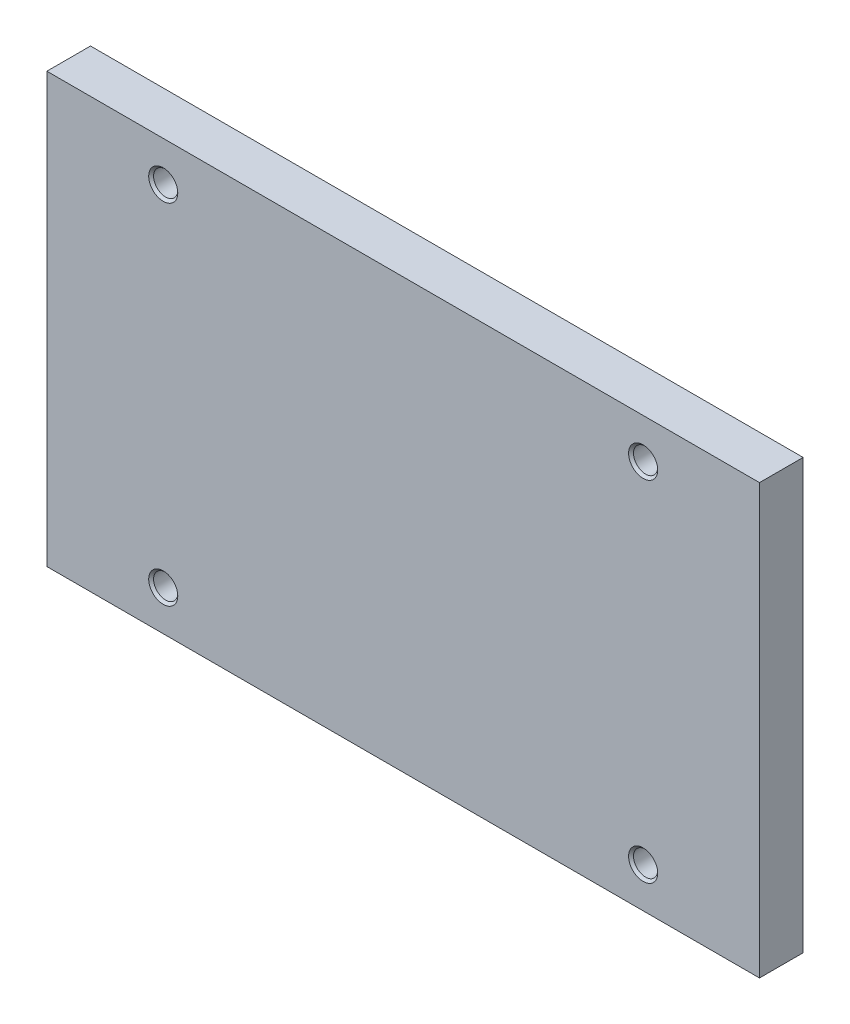
SolidWorks part; units mm, degrees
ref_plane "Спереди" through (0, 0, 0) normal (0, 0, 1) x (1, 0, 0)
ref_plane "Сверху" through (0, 0, 0) normal (0, 1, 0) x (1, 0, 0)
ref_plane "Справа" through (0, 0, 0) normal (1, 0, 0) x (0, 0, -1)
ref_plane "Плоскость4" through (0, 0, 12) normal (0, 0, 1) x (1, 0, 0)
sketch "Эскиз1" plane through (0, 0, 12) normal (0, 0, 1) x (1, 0, 0)
  line L0 (98, 59) -> (-98, 59)
  line L1 (-98, 59) -> (-98, -59)
  line L2 (-98, -59) -> (98, -59)
  line L3 (98, -59) -> (98, 59)
extrude "Бобышка-Вытянуть1" add sketch "Эскиз1" against normal blind 12
hole_wizard "Отверстие с зазором M61" positions "Эскиз3" profile "Эскиз2" hole size "M6" standard "Ansi Metric"
sketch "Эскиз3" plane through (0, 0, 0) normal (0, 0, -1) x (-1, 0, 0)
  point P0 (-66, -48)
sketch "Эскиз2" plane through (66, -48, 0) normal (1, 0, 0) x (0, 1, 0)
  line L0 (0, 0) -> (0, 12)
  line L1 (0, 12) -> (3.3235, 12)
  line L2 (3.3235, 12) -> (3.3235, 0)
  line L5 (3.3235, 0) -> (0, 0)
  line L11 (0, -6.35) -> (0, 107.95) construction
  dimension "Диаметр сквозного отверстия" = 6.647
  dimension "Глубина сквозного отверстия" = 12
hole_wizard "Отверстие с зазором M62" positions "Эскиз5" profile "Эскиз4" hole size "M6" standard "Ansi Metric"
sketch "Эскиз5" plane through (0, 0, 12) normal (0, 0, 1) x (1, 0, 0)
  point P0 (-66, 48)
  point P1 (-66, -48)
  point P2 (66, 48)
sketch "Эскиз4" plane through (-66, 48, 12) normal (1, 0, 0) x (0, -1, 0)
  line L0 (0, 0) -> (0, 12)
  line L1 (0, 12) -> (3.3235, 12)
  line L2 (3.3235, 12) -> (3.3235, 0)
  line L5 (3.3235, 0) -> (0, 0)
  line L11 (0, -6.35) -> (0, 107.95) construction
  dimension "Диаметр сквозного отверстия" = 6.647
  dimension "Глубина сквозного отверстия" = 12
chamfer "Фаска1" distance 0.6765 angle 45 8 edges at (62.6765, -48, 12) (69.3235, 48, 0) (69.3235, 48, 12) (-62.6765, 48, 0) (62.6765, -48, 0) (-62.6765, -48, 0) (-62.6765, 48, 12) (-62.6765, -48, 12)
